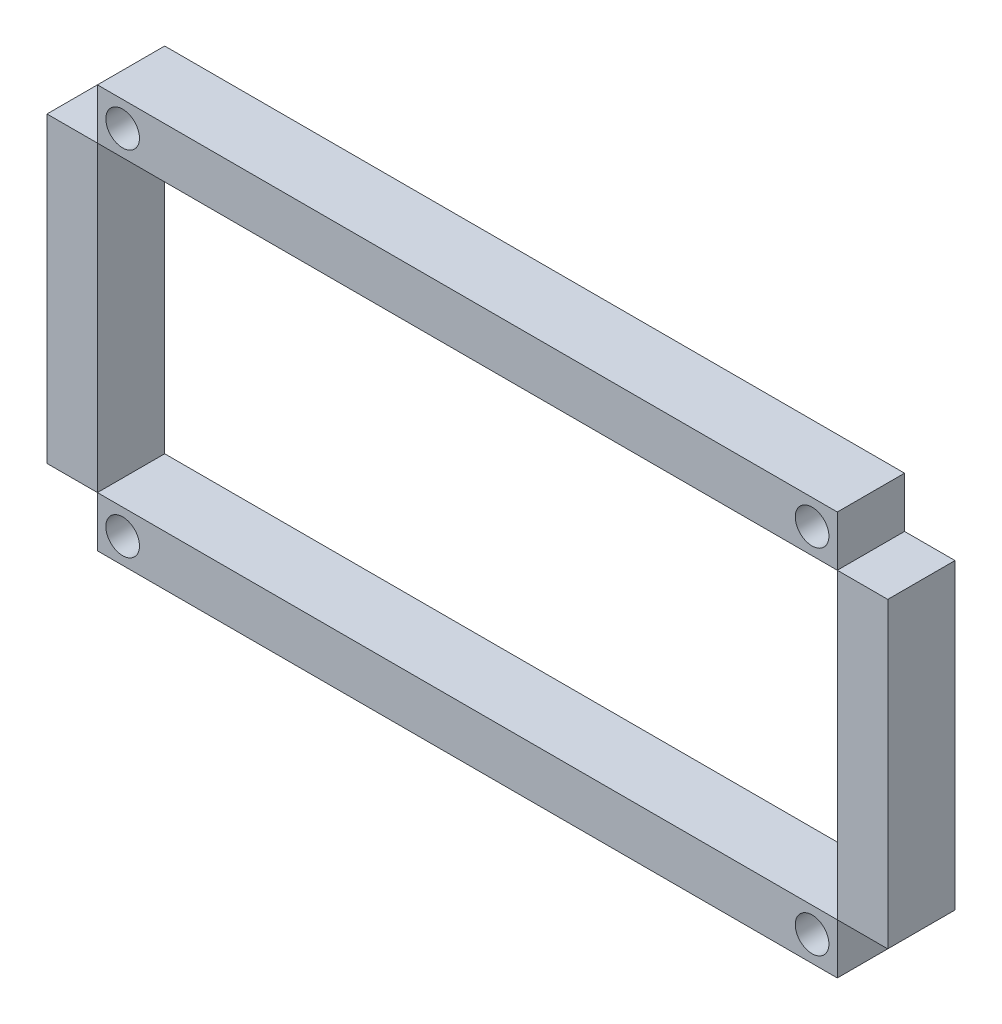
SolidWorks part; units mm, degrees
ref_plane "前视基准面" through (0, 0, 0) normal (0, 0, 1) x (1, 0, 0)
ref_plane "上视基准面" through (0, 0, 0) normal (0, 1, 0) x (1, 0, 0)
ref_plane "右视基准面" through (0, 0, 0) normal (1, 0, 0) x (0, 0, -1)
other "Configuration Table"
sketch "草图1" plane through (0, 0, 0) normal (0, 0, 1) x (1, 0, 0)
  line L0 (-44.0952, 52.3673) -> (-44.0952, 22.3673) construction
  line L1 (-59.0952, -157.6327) -> (380.9048, -157.6327)
  line L2 (-59.0952, -157.6327) -> (-59.0952, -187.6327)
  line L3 (-59.0952, -187.6327) -> (380.9048, -187.6327)
  line L4 (380.9048, -157.6327) -> (380.9048, -187.6327)
  line L5 (-89.0952, -157.6327) -> (-59.0952, -157.6327)
  line L6 (-89.0952, -157.6327) -> (-89.0952, 22.3673)
  line L7 (-89.0952, 22.3673) -> (-59.0952, 22.3673)
  line L8 (-59.0952, -157.6327) -> (-59.0952, 22.3673)
  line L9 (-59.0952, 22.3673) -> (380.9048, 22.3673)
  line L10 (-59.0952, 22.3673) -> (-59.0952, 52.3673)
  line L11 (-59.0952, 52.3673) -> (380.9048, 52.3673)
  line L12 (380.9048, 22.3673) -> (380.9048, 52.3673)
  line L13 (380.9048, 22.3673) -> (410.9048, 22.3673)
  line L14 (380.9048, 22.3673) -> (380.9048, -157.6327)
  line L15 (380.9048, -157.6327) -> (410.9048, -157.6327)
  line L16 (410.9048, 22.3673) -> (410.9048, -157.6327)
  line L17 (-44.0952, -157.6327) -> (-44.0952, -187.6327) construction
  circle A0 centre (-44.0952, 37.3673) radius 10
  circle A1 centre (-44.0952, 37.3673) radius 10
  circle A2 centre (365.9048, 37.3673) radius 10
  circle A3 centre (365.9048, -172.6327) radius 10
  circle A4 centre (-44.0952, -172.6327) radius 10
  dimension "D4" = 15
  dimension "D5" = 15
  dimension "D7" = 180
  dimension "D1" = 30
  dimension "D2" = 410
  dimension "D3" = 210
  dimension "D6" = 440
  dimension "D8" = 440
extrude "凸台-拉伸3" add sketch "草图1" along normal blind 40 contours L9 L12 L11 L10 A2 A0 | L5 L8 L7 L6 | L16 L13 L14 L15 | L4 L1 L2 L3 A4 A3
